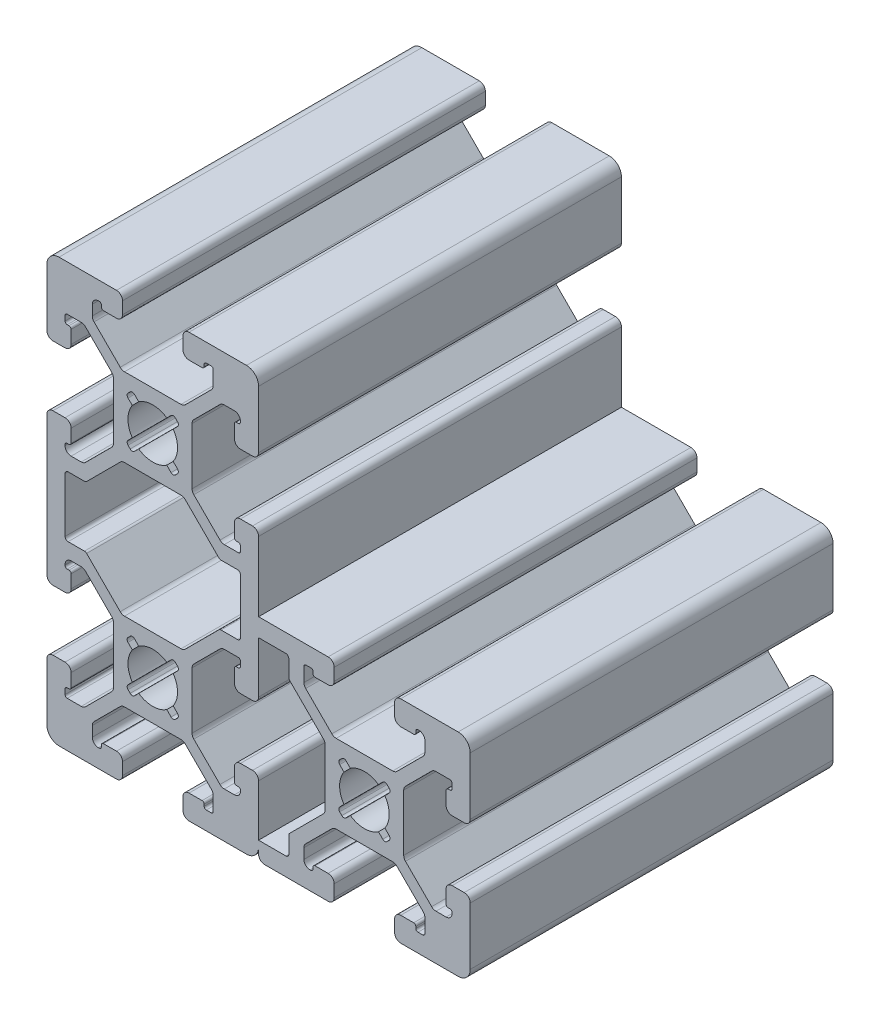
SolidWorks part; units mm, degrees
ref_plane "Ön Düzlem" through (0, 0, 0) normal (0, 0, 1) x (1, 0, 0)
ref_plane "Üst Düzlem" through (0, 0, 0) normal (0, 1, 0) x (1, 0, 0)
ref_plane "Sağ Düzlem" through (0, 0, 0) normal (1, 0, 0) x (0, 0, -1)
sketch "Çizim1" plane through (0, 0, 0) normal (0, 0, 1) x (1, 0, 0)
  line L1 (-35, -35) -> (35, -35) construction
  line L2 (-35, -35) -> (-35, 35) construction
  line L3 (-35, 35) -> (35, 35) construction
  line L4 (35, -35) -> (35, 35) construction
  line L5 (0, 35) -> (0, -35) construction
  line L6 (-35, 0) -> (35, 0) construction
  point P0 (0, 0)
  dimension "D1" = 70
  dimension "D2" = 70
sketch "Çizim3" plane through (0, 0, 0) normal (0, 0, 1) x (1, 0, 0)
  line L0 (-17.5, 35) -> (-17.5, 0) construction
  line L1 (-35, 35) -> (35, 35) construction
  line L2 (-35, 0) -> (35, 0) construction
  line L3 (-35, 17.5) -> (0, 17.5) construction
  line L4 (-35, -35) -> (-35, 35) construction
  line L5 (0, 35) -> (0, -35) construction
  line L6 (-12.5, 34) -> (-12.5, 32)
  line L7 (-11.5, 31) -> (-9.35, 31)
  line L8 (-9, 31.35) -> (-9, 31.65)
  line L9 (-8.65, 32) -> (-7.85, 32)
  line L10 (-7.5, 31.65) -> (-7.5, 29.3284)
  line L11 (-7.7929, 28.6213) -> (-12.1213, 24.2929)
  line L12 (-12.8284, 24) -> (-17.5, 24)
  line L13 (-11.5, 35) -> (-2, 35)
  line L14 (-17.5, 17.5) -> (0, 35) construction
  line L17 (-11, 22.1716) -> (-11, 17.5)
  line L18 (-6.3787, 27.2071) -> (-10.7071, 22.8787)
  line L19 (-4, 27.5) -> (-5.6716, 27.5)
  line L20 (-3, 26.35) -> (-3, 26.5)
  line L21 (-3.65, 26) -> (-3.35, 26)
  line L22 (-4, 23.5) -> (-4, 25.65)
  line L23 (-1, 22.5) -> (-3, 22.5)
  line L24 (0, 23.5) -> (0, 33)
  line L32 (-12.8284, 11) -> (-17.5, 11)
  line L35 (-11, 12.8284) -> (-11, 17.5)
  line L36 (-6.3787, 7.7929) -> (-10.7071, 12.1213)
  line L37 (-3.35, 7.5) -> (-5.6716, 7.5)
  line L38 (-3, 8.65) -> (-3, 7.85)
  line L39 (-3.65, 9) -> (-3.35, 9)
  line L40 (-4, 11.5) -> (-4, 9.35)
  line L41 (-1, 12.5) -> (-3, 12.5)
  line L43 (-17.5, 17.5) -> (0, 0) construction
  line L45 (-34, 12.5) -> (-32, 12.5)
  line L46 (-31, 11.5) -> (-31, 9.35)
  line L47 (-31.35, 9) -> (-31.65, 9)
  line L48 (-32, 8.65) -> (-32, 8.5)
  line L49 (-31, 7.5) -> (-29.3284, 7.5)
  line L50 (-28.6213, 7.7929) -> (-24.2929, 12.1213)
  line L51 (-24, 12.8284) -> (-24, 17.5)
  line L54 (-22.1716, 11) -> (-17.5, 11)
  line L62 (-17.5, 17.5) -> (-35, 0) construction
  line L63 (-23.5, 35) -> (-33, 35)
  line L64 (-22.5, 34) -> (-22.5, 32)
  line L65 (-23.5, 31) -> (-25.65, 31)
  line L66 (-26, 31.35) -> (-26, 31.65)
  line L67 (-26.35, 32) -> (-26.5, 32)
  line L68 (-27.5, 31) -> (-27.5, 29.3284)
  line L69 (-27.2071, 28.6213) -> (-22.8787, 24.2929)
  line L70 (-22.1716, 24) -> (-17.5, 24)
  line L73 (-24, 22.1716) -> (-24, 17.5)
  line L74 (-28.6213, 27.2071) -> (-24.2929, 22.8787)
  line L75 (-31.65, 27.5) -> (-29.3284, 27.5)
  line L76 (-32, 26.35) -> (-32, 27.15)
  line L77 (-31.35, 26) -> (-31.65, 26)
  line L78 (-31, 23.5) -> (-31, 25.65)
  line L79 (-34, 22.5) -> (-32, 22.5)
  line L80 (-35, 23.5) -> (-35, 33)
  line L81 (-17.5, 17.5) -> (-35, 35) construction
  line L82 (-27.5, 3.35) -> (-27.5, 5.6716) [skipped]
  line L83 (-26.35, 3) -> (-27.15, 3) [skipped]
  line L84 (-26, 3.65) -> (-26, 3.35) [skipped]
  line L85 (-23.5, 4) -> (-25.65, 4) [skipped]
  line L86 (-22.5, 1) -> (-22.5, 3) [skipped]
  line L87 (-23.5, 0) -> (-33, 0) [skipped]
  line L88 (-32, 0) -> (-32, 4.5)
  line L89 (-31.5, 5) -> (-28.7929, 5)
  line L90 (-28.4393, 5.1464) -> (-22.8787, 10.7071)
  line L91 (-35, 11.5) -> (-35, 0)
  line L92 (-27.2071, 6.3787) -> (-22.8787, 10.7071) [skipped]
  line L93 (-35, 11.5) -> (-35, 2) [skipped]
  line L94 (-35, 0) -> (-32, 0)
  line L95 (0, 0) -> (-3, 0)
  line L96 (-11.5, 0) -> (-2, 0) [skipped]
  line L97 (-12.5, 1) -> (-12.5, 3) [skipped]
  line L98 (-11.5, 4) -> (-9.35, 4) [skipped]
  line L99 (-9, 3.65) -> (-9, 3.35) [skipped]
  line L100 (-8.65, 3) -> (-8.5, 3) [skipped]
  line L101 (-7.5, 4) -> (-7.5, 5.6716) [skipped]
  line L102 (-7.7929, 6.3787) -> (-12.1213, 10.7071) [skipped]
  line L103 (-3, 0) -> (-3, 4.5)
  line L104 (-3.5, 5) -> (-6.2071, 5)
  line L105 (-6.5607, 5.1464) -> (-12.1213, 10.7071)
  line L106 (0, 11.5) -> (0, 2) [skipped]
  line L107 (0, 11.5) -> (0, 0)
  line L109 (-15.1801, 20.8805) -> (-14.1195, 19.8199) construction
  line L110 (-15.1801, 20.8805) -> (-14.473, 21.5877)
  line L111 (-14.1195, 19.8199) -> (-13.4123, 20.527)
  line L112 (-13.7659, 21.5877) -> (-13.4123, 21.2341)
  line L113 (-14.1195, 15.1801) -> (-13.4123, 14.473)
  line L114 (-13.4123, 13.7659) -> (-13.7659, 13.4123)
  line L115 (-15.1801, 14.1195) -> (-14.473, 13.4123)
  line L116 (-19.8199, 14.1195) -> (-20.527, 13.4123)
  line L117 (-21.2341, 13.4123) -> (-21.5877, 13.7659)
  line L118 (-20.8805, 15.1801) -> (-21.5877, 14.473)
  line L119 (-20.8805, 19.8199) -> (-21.5877, 20.527)
  line L120 (-21.5877, 21.2341) -> (-21.2341, 21.5877)
  line L121 (-19.8199, 20.8805) -> (-20.527, 21.5877)
  arc A0 (-7.5, 29.3284) -> (-7.7929, 28.6213) centre (-8.5, 29.3284) cw
  arc A1 (-12.5, 32) -> (-11.5, 31) centre (-11.5, 32) ccw
  arc A2 (-12.5, 34) -> (-11.5, 35) centre (-11.5, 34) cw
  arc A3 (-1, 22.5) -> (0, 23.5) centre (-1, 23.5) ccw
  arc A4 (-4, 23.5) -> (-3, 22.5) centre (-3, 23.5) ccw
  arc A5 (-12.1213, 24.2929) -> (-12.8284, 24) centre (-12.8284, 25) cw
  arc A6 (-2, 35) -> (0, 33) centre (-2, 33) cw
  arc A7 (-7.85, 32) -> (-7.5, 31.65) centre (-7.85, 31.65) cw
  arc A8 (-9, 31.65) -> (-8.65, 32) centre (-8.65, 31.65) cw
  arc A9 (-9.35, 31) -> (-9, 31.35) centre (-9.35, 31.35) ccw
  arc A10 (-4, 27.5) -> (-3, 26.5) centre (-4, 26.5) cw
  arc A11 (-6.3787, 27.2071) -> (-5.6716, 27.5) centre (-5.6716, 26.5) cw
  arc A12 (-11, 22.1716) -> (-10.7071, 22.8787) centre (-10, 22.1716) cw
  arc A13 (-3, 26.35) -> (-3.35, 26) centre (-3.35, 26.35) cw
  arc A14 (-3.65, 26) -> (-4, 25.65) centre (-3.65, 25.65) ccw
  arc A22 (-12.8284, 11) -> (-12.1213, 10.7071) centre (-12.8284, 10) cw
  arc A23 (-10.7071, 12.1213) -> (-11, 12.8284) centre (-10, 12.8284) cw
  arc A24 (-5.6716, 7.5) -> (-6.3787, 7.7929) centre (-5.6716, 8.5) cw
  arc A25 (-3, 7.85) -> (-3.35, 7.5) centre (-3.35, 7.85) cw
  arc A26 (-3.35, 9) -> (-3, 8.65) centre (-3.35, 8.65) cw
  arc A27 (-4, 9.35) -> (-3.65, 9) centre (-3.65, 9.35) ccw
  arc A28 (-3, 12.5) -> (-4, 11.5) centre (-3, 11.5) ccw
  arc A29 (-1, 12.5) -> (0, 11.5) centre (-1, 11.5) cw
  arc A31 (-34, 12.5) -> (-35, 11.5) centre (-34, 11.5) ccw
  arc A32 (-31, 11.5) -> (-32, 12.5) centre (-32, 11.5) ccw
  arc A33 (-31.35, 9) -> (-31, 9.35) centre (-31.35, 9.35) ccw
  arc A34 (-32, 8.65) -> (-31.65, 9) centre (-31.65, 8.65) cw
  arc A35 (-31, 7.5) -> (-32, 8.5) centre (-31, 8.5) cw
  arc A36 (-28.6213, 7.7929) -> (-29.3284, 7.5) centre (-29.3284, 8.5) cw
  arc A37 (-24, 12.8284) -> (-24.2929, 12.1213) centre (-25, 12.8284) cw
  arc A38 (-22.8787, 10.7071) -> (-22.1716, 11) centre (-22.1716, 10) cw
  arc A45 (-35, 33) -> (-33, 35) centre (-33, 33) cw
  arc A46 (-22.5, 34) -> (-23.5, 35) centre (-23.5, 34) ccw
  arc A47 (-23.5, 31) -> (-22.5, 32) centre (-23.5, 32) ccw
  arc A48 (-26, 31.35) -> (-25.65, 31) centre (-25.65, 31.35) ccw
  arc A49 (-26.35, 32) -> (-26, 31.65) centre (-26.35, 31.65) cw
  arc A50 (-27.5, 31) -> (-26.5, 32) centre (-26.5, 31) cw
  arc A51 (-27.2071, 28.6213) -> (-27.5, 29.3284) centre (-26.5, 29.3284) cw
  arc A52 (-22.1716, 24) -> (-22.8787, 24.2929) centre (-22.1716, 25) cw
  arc A53 (-24.2929, 22.8787) -> (-24, 22.1716) centre (-25, 22.1716) cw
  arc A54 (-29.3284, 27.5) -> (-28.6213, 27.2071) centre (-29.3284, 26.5) cw
  arc A55 (-32, 27.15) -> (-31.65, 27.5) centre (-31.65, 27.15) cw
  arc A56 (-31.65, 26) -> (-32, 26.35) centre (-31.65, 26.35) cw
  arc A57 (-31, 25.65) -> (-31.35, 26) centre (-31.35, 25.65) ccw
  arc A58 (-32, 22.5) -> (-31, 23.5) centre (-32, 23.5) ccw
  arc A59 (-34, 22.5) -> (-35, 23.5) centre (-34, 23.5) cw
  arc A60 (-27.15, 3) -> (-27.5, 3.35) centre (-27.15, 3.35) cw [skipped]
  arc A61 (-26, 3.35) -> (-26.35, 3) centre (-26.35, 3.35) cw [skipped]
  arc A62 (-25.65, 4) -> (-26, 3.65) centre (-25.65, 3.65) ccw [skipped]
  arc A63 (-22.5, 3) -> (-23.5, 4) centre (-23.5, 3) ccw [skipped]
  arc A64 (-22.5, 1) -> (-23.5, 0) centre (-23.5, 1) cw [skipped]
  arc A65 (-27.5, 5.6716) -> (-27.2071, 6.3787) centre (-26.5, 5.6716) cw [skipped]
  arc A66 (-33, 0) -> (-35, 2) centre (-33, 2) cw [skipped]
  arc A67 (-12.5, 1) -> (-11.5, 0) centre (-11.5, 1) ccw [skipped]
  arc A68 (-11.5, 4) -> (-12.5, 3) centre (-11.5, 3) ccw [skipped]
  arc A69 (-9, 3.65) -> (-9.35, 4) centre (-9.35, 3.65) ccw [skipped]
  arc A70 (-8.65, 3) -> (-9, 3.35) centre (-8.65, 3.35) cw [skipped]
  arc A71 (-7.5, 4) -> (-8.5, 3) centre (-8.5, 4) cw [skipped]
  arc A72 (0, 2) -> (-2, 0) centre (-2, 2) cw [skipped]
  arc A73 (-7.7929, 6.3787) -> (-7.5, 5.6716) centre (-8.5, 5.6716) cw [skipped]
  arc A74 (-28.7929, 5) -> (-28.4393, 5.1464) centre (-28.7929, 5.5) ccw
  arc A75 (-32, 4.5) -> (-31.5, 5) centre (-31.5, 4.5) cw
  arc A76 (-3, 4.5) -> (-3.5, 5) centre (-3.5, 4.5) ccw
  arc A77 (-6.2071, 5) -> (-6.5607, 5.1464) centre (-6.2071, 5.5) cw
  circle A78 centre (-17.5, 17.5) radius 4.1 construction
  arc A79 (-13.4123, 20.527) -> (-13.4123, 21.2341) centre (-13.7659, 20.8805) ccw
  arc A80 (-14.473, 21.5877) -> (-13.7659, 21.5877) centre (-14.1195, 21.2341) cw
  arc A81 (-13.4123, 14.473) -> (-13.4123, 13.7659) centre (-13.7659, 14.1195) cw
  arc A82 (-14.473, 13.4123) -> (-13.7659, 13.4123) centre (-14.1195, 13.7659) ccw
  circle A83 centre (-17.5, 17.5) radius 4.1 construction
  arc A84 (-20.527, 13.4123) -> (-21.2341, 13.4123) centre (-20.8805, 13.7659) cw
  arc A85 (-21.5877, 14.473) -> (-21.5877, 13.7659) centre (-21.2341, 14.1195) ccw
  circle A86 centre (-17.5, 17.5) radius 4.1 construction
  arc A87 (-21.5877, 20.527) -> (-21.5877, 21.2341) centre (-21.2341, 20.8805) cw
  arc A88 (-20.527, 21.5877) -> (-21.2341, 21.5877) centre (-20.8805, 21.2341) ccw
  circle A89 centre (-17.5, 17.5) radius 4.1 construction
  arc A90 (-19.8199, 20.8805) -> (-15.1801, 20.8805) centre (-17.5, 17.5) cw
  arc A91 (-14.1195, 19.8199) -> (-14.1195, 15.1801) centre (-17.5, 17.5) cw
  arc A92 (-19.8199, 14.1195) -> (-15.1801, 14.1195) centre (-17.5, 17.5) ccw
  arc A93 (-20.8805, 15.1801) -> (-20.8805, 19.8199) centre (-17.5, 17.5) cw
  point P32 (-7.5, 28.9142)
  point P35 (-12.5, 31)
  point P38 (-12.5, 35)
  point P41 (0, 22.5)
  point P44 (-4, 22.5)
  point P47 (-12.4142, 24)
  point P53 (-7.5, 32)
  point P56 (-9, 32)
  point P59 (-9, 31)
  point P62 (-3, 27.5)
  point P65 (-6.0858, 27.5)
  point P68 (-11, 22.5858)
  point P71 (-3, 26)
  point P74 (-4, 26)
  point P86 (-14.6498, 20.3502)
  point P125 (-13.0588, 20.8805)
  point P129 (-14.1195, 21.9412)
  point P222 (-17.5, 17.5)
  point P305 (-17.5, 17.5)
  dimension "D10" = 1
  dimension "D11" = 2
  dimension "D12" = 0.35
  dimension "D13" = 1
  dimension "D14" = 0.35
  dimension "D17" = 0.5
  dimension "D21" = 0.5
  dimension "D22" = 0.5
  dimension "D23" = 8.2
  dimension "D26" = 0.5
  dimension "D1" = 17.5
  dimension "D2" = 17.5
  dimension "D3" = 5
  dimension "D4" = 1
  dimension "D5" = 3
  dimension "D6" = 4
  dimension "D7" = 3.5
  dimension "D8" = 7.5
  dimension "D9" = 6.5
  dimension "D16" = 5
  dimension "D18" = 2.5
  dimension "D19" = 3
  dimension "D20" = 11.2929
  dimension "D24" = 1.5
  dimension "D25" = 1.5
  dimension "D15" = 4
  dimension "D27" = 4
extrude "Yükseklik-Ekstrüzyon1" add sketch "Çizim3" against normal blind 60
mirror "Aynalama1" about plane through (-35, 0, -60) normal (0, -1, 0) of bodies 101
move or copy body "Gövde-Taşı/Kopyala1" bodies to move or copy 102 copy yes number of copies 1 rotation origin (0, 0, 0) rotation axis (0, 0, 1) rotation angle 90
combine bodies "Combine1" operation type add bodies to combine 102 101 103
fillet "Fillet1" radius 1 1 edges at (0, -35, -30)
